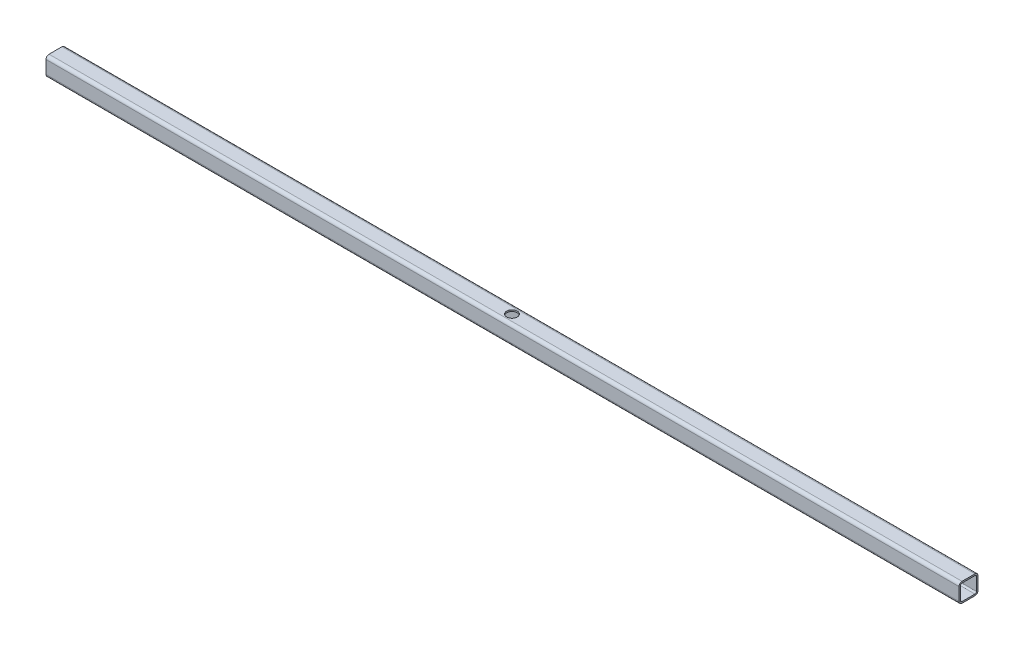
SolidWorks part; units mm, degrees
ref_plane "Front Plane" through (0, 0, 0) normal (0, 0, 1) x (1, 0, 0)
ref_plane "Top Plane" through (0, 0, 0) normal (0, 1, 0) x (1, 0, 0)
ref_plane "Right Plane" through (0, 0, 0) normal (1, 0, 0) x (0, 0, -1)
sketch "Sketch1" plane through (0, 0, 0) normal (0, 1, 0) x (1, 0, 0)
  line L0 (0, 0) -> (1920, 0)
  dimension "D1" = 1920
other "Tube (square) 40 X 40 X 3.2(4)"
ref_plane "Plane1" through (0, 0, 0) normal (1, 0, 0) x (0, 0, -1)
sketch "Sketch12" plane through (0, 0, 0) normal (1, 0, 0) x (0, 0, -1)
  line L0 (-13.6, -16.8) -> (13.6, -16.8)
  line L1 (-16.8, -13.6) -> (-16.8, 13.6)
  line L2 (13.6, 16.8) -> (-13.6, 16.8)
  line L3 (16.8, 13.6) -> (16.8, -13.6)
  line L4 (-13.6, -20) -> (13.6, -20)
  line L5 (-20, -13.6) -> (-20, 13.6)
  line L6 (13.6, 20) -> (-13.6, 20)
  line L7 (20, 13.6) -> (20, -13.6)
  line L8 (-20, 0) -> (-16.8, 0) construction
  line L9 (-16.8, 0) -> (16.8, 0) construction
  line L10 (16.8, 0) -> (20, 0) construction
  line L12 (0, 20) -> (0, 16.8) construction
  line L13 (0, 16.8) -> (0, -16.8) construction
  line L14 (0, -16.8) -> (0, -20) construction
  arc A0 (20, 13.6) -> (13.6, 20) centre (13.6, 13.6) ccw
  arc A1 (13.6, -20) -> (20, -13.6) centre (13.6, -13.6) ccw
  arc A2 (-20, -13.6) -> (-13.6, -20) centre (-13.6, -13.6) ccw
  arc A3 (-13.6, 20) -> (-20, 13.6) centre (-13.6, 13.6) ccw
  arc A4 (-13.6, 16.8) -> (-16.8, 13.6) centre (-13.6, 13.6) ccw
  arc A5 (16.8, 13.6) -> (13.6, 16.8) centre (13.6, 13.6) ccw
  arc A6 (13.6, -16.8) -> (16.8, -13.6) centre (13.6, -13.6) ccw
  arc A7 (-16.8, -13.6) -> (-13.6, -16.8) centre (-13.6, -13.6) ccw
  point P2 (-20, 20)
  point P33 (-20, -20)
  point P34 (20, -20)
  point P36 (20, 20)
  point P37 (0, 0)
  dimension "D1" = 6.4
  dimension "Thickness" = 3.2
  dimension "V_leg" = 40
  dimension "H_leg" = 40
ref_plane "Plane2" through (0, 20, 0) normal (0, 1, 0) x (1, 0, 0)
sketch "Sketch13" plane through (0, 20, 0) normal (0, 1, 0) x (1, 0, 0)
  line L0 (960, 13.6) -> (960, -13.6) construction
  line L4 (0, 13.6) -> (0, -13.6)
  line L5 (0, -13.6) -> (1920, -13.6)
  line L6 (1920, -13.6) -> (1920, 13.6)
  line L7 (1920, 13.6) -> (0, 13.6)
  line L8 (0, 13.6) -> (0, -13.6) construction
  line L9 (0, -13.6) -> (1920, -13.6) construction
  line L10 (1920, -13.6) -> (1920, 13.6) construction
  line L11 (1920, 13.6) -> (0, 13.6) construction
  circle A0 centre (960, 0) radius 11
  dimension "D1" = 0
extrude "Cut-Extrude1" cut sketch "Sketch13" against normal through all
